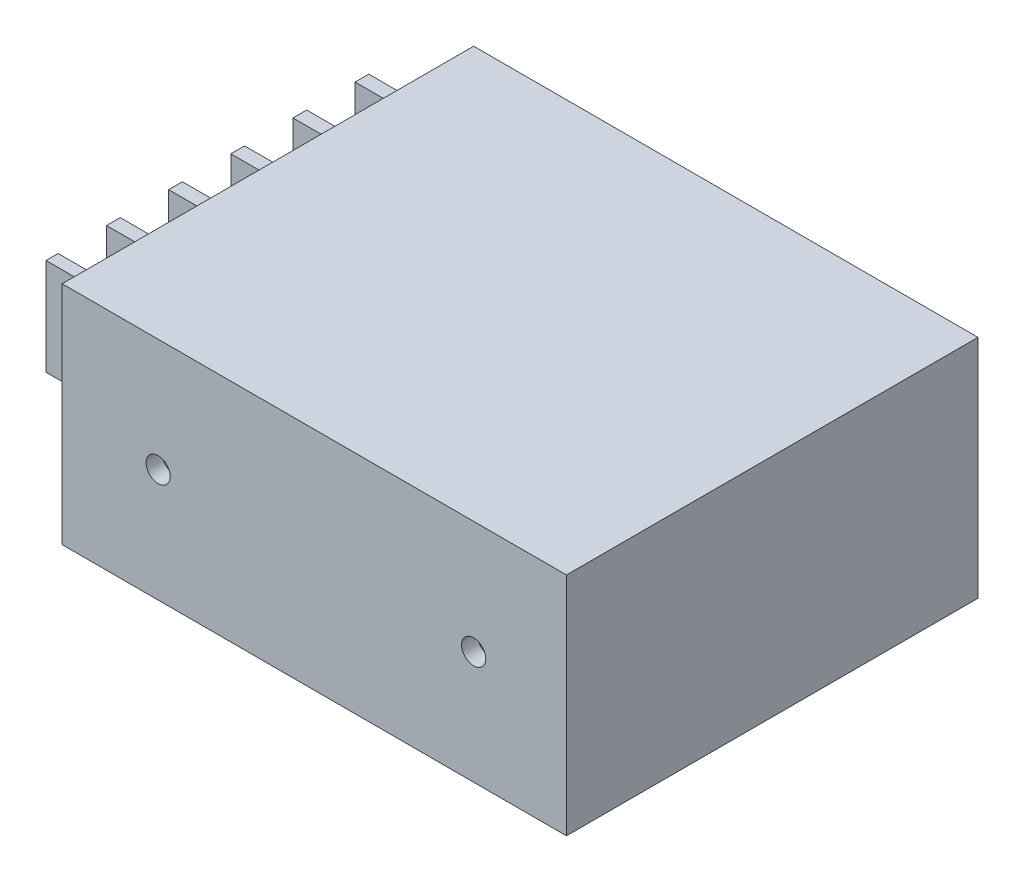
SolidWorks part; units mm, degrees
ref_plane "Спереди" through (0, 0, 0) normal (0, 0, 1) x (1, 0, 0)
ref_plane "Сверху" through (0, 0, 0) normal (0, 1, 0) x (1, 0, 0)
ref_plane "Справа" through (0, 0, 0) normal (1, 0, 0) x (0, 0, -1)
sketch "Эскиз2" plane through (0, 0, 0) normal (0, 1, 0) x (1, 0, 0)
  line L1 (-31.25, -25.5) -> (31.25, -25.5)
  line L2 (-31.25, -25.5) -> (-31.25, 25.5)
  line L3 (-31.25, 25.5) -> (31.25, 25.5)
  line L4 (31.25, -25.5) -> (31.25, 25.5)
  line L5 (-31.25, -25.5) -> (31.25, 25.5) construction
  line L6 (-31.25, 25.5) -> (31.25, -25.5) construction
  point P0 (0, 0)
  dimension "D1" = 62.5
  dimension "D2" = 51
extrude "Бобышка-Вытянуть1" add sketch "Эскиз2" along normal blind 28
sketch "Эскиз3" plane through (-31.25, 0, 0) normal (-1, 0, 0) x (0, 0, 1)
  line L0 (-25.5, 28) -> (-25.5, 0) construction
  line L1 (-25.5, 18.5) -> (14.5, 18.5)
  line L2 (-25.5, 18.5) -> (-25.5, 6.5)
  line L3 (-25.5, 6.5) -> (14.5, 6.5)
  line L4 (14.5, 18.5) -> (14.5, 6.5)
  line L5 (-25.5, 18.5) -> (14.5, 6.5) construction
  line L6 (-25.5, 6.5) -> (14.5, 18.5) construction
  line L7 (-25.5, 0) -> (25.5, 0) construction
  point P4 (-5.5, 12.5)
  dimension "D1" = 12
  dimension "D2" = 40
  dimension "D3" = 6.5
extrude "Бобышка-Вытянуть2" add sketch "Эскиз3" along normal blind 13
sketch "Эскиз4" plane through (-44.25, 0, 0) normal (-1, 0, 0) x (0, 0, 1)
  line L0 (14.5, 18.5) -> (-25.5, 18.5) construction
  line L1 (-23.8, 18.5) -> (-17.8, 18.5)
  line L2 (-23.8, 18.5) -> (-23.8, 6.5)
  line L3 (-23.8, 6.5) -> (-17.8, 6.5)
  line L4 (-17.8, 18.5) -> (-17.8, 6.5)
  line L5 (-23.8, 18.5) -> (-17.8, 6.5) construction
  line L6 (-23.8, 6.5) -> (-17.8, 18.5) construction
  line L7 (-25.5, 6.5) -> (14.5, 6.5) construction
  line L8 (-25.5, 6.5) -> (14.5, 6.5) construction
  line L9 (-16.1, 18.5) -> (-10.1, 18.5)
  line L10 (-16.1, 18.5) -> (-16.1, 6.5)
  line L11 (-16.1, 6.5) -> (-10.1, 6.5)
  line L12 (-10.1, 18.5) -> (-10.1, 6.5)
  line L13 (-16.1, 18.5) -> (-10.1, 6.5) construction
  line L14 (-16.1, 6.5) -> (-10.1, 18.5) construction
  line L15 (-8.4, 18.5) -> (-2.4, 18.5)
  line L16 (-8.4, 18.5) -> (-8.4, 6.5)
  line L17 (-8.4, 6.5) -> (-2.4, 6.5)
  line L18 (-2.4, 18.5) -> (-2.4, 6.5)
  line L19 (-8.4, 18.5) -> (-2.4, 6.5) construction
  line L20 (-8.4, 6.5) -> (-2.4, 18.5) construction
  line L21 (-25.5, 18.5) -> (-25.5, 6.5) construction
  line L22 (-0.7, 18.5) -> (5.3, 18.5)
  line L23 (-0.7, 18.5) -> (-0.7, 6.5)
  line L24 (-0.7, 6.5) -> (5.3, 6.5)
  line L25 (5.3, 18.5) -> (5.3, 6.5)
  line L26 (-0.7, 18.5) -> (5.3, 6.5) construction
  line L27 (-0.7, 6.5) -> (5.3, 18.5) construction
  line L28 (7, 18.5) -> (13, 18.5)
  line L29 (7, 18.5) -> (7, 6.5)
  line L30 (7, 6.5) -> (13, 6.5)
  line L31 (13, 18.5) -> (13, 6.5)
  line L32 (7, 18.5) -> (13, 6.5) construction
  line L33 (7, 6.5) -> (13, 18.5) construction
  point P4 (-20.8, 12.5)
  point P13 (-13.1, 12.5)
  point P18 (-5.4, 12.5)
  point P25 (2.3, 12.5)
  point P30 (10, 12.5)
  dimension "D1" = 6
  dimension "D2" = 1.7
  dimension "D4" = 1.7
  dimension "D5" = 1.7
  dimension "D6" = 1.7
  dimension "D3" = 1.7
extrude "Вырез-Вытянуть1" cut sketch "Эскиз4" against normal blind 10
sketch "Эскиз5" plane through (0, 0, 0) normal (0, -1, 0) x (1, 0, 0)
  line L1 (31.25, 25.5) -> (31.25, -25.5) construction
  circle A0 centre (-22.5, 0) radius 1.5
  circle A1 centre (16.6, 0) radius 1.5
  dimension "D3" = 3
  dimension "D1" = 14.65
  dimension "D2" = 39.1
extrude "Вырез-Вытянуть2" cut sketch "Эскиз5" against normal blind 2
sketch "Эскиз6" plane through (0, 0, 25.5) normal (0, 0, 1) x (1, 0, 0)
  line L1 (31.25, 28) -> (31.25, 0) construction
  circle A0 centre (-19.35, 14) radius 1.5
  circle A1 centre (19.75, 14) radius 1.5
  dimension "D2" = 3
  dimension "D1" = 14
  dimension "D3" = 11.5
  dimension "D4" = 39.1
extrude "Вырез-Вытянуть3" cut sketch "Эскиз6" against normal blind 2
sketch "Эскиз7" plane through (-31.25, 0, 0) normal (-1, 0, 0) x (0, 0, 1)
  line L0 (-23.7764, 21.5382) -> (13.2265, 21.5382) construction
  line L1 (-23.7764, 18.9444) -> (-17.9944, 18.9444)
  line L2 (-23.7764, 18.9444) -> (-23.7764, 27.05)
  line L3 (-23.7764, 27.05) -> (-17.9944, 27.05)
  line L4 (-17.9944, 18.9444) -> (-17.9944, 27.05)
  line L5 (-15.941, 18.9444) -> (-10.2671, 18.9444)
  line L6 (-15.941, 18.9444) -> (-15.941, 27.05)
  line L7 (-15.941, 27.05) -> (-10.2671, 27.05)
  line L8 (-10.2671, 18.9444) -> (-10.2671, 27.05)
  line L9 (-8.4839, 18.9444) -> (-2.4086, 18.9444)
  line L10 (-8.4839, 18.9444) -> (-8.4839, 27.05)
  line L11 (-8.4839, 27.05) -> (-2.4086, 27.05)
  line L12 (-2.4086, 18.9444) -> (-2.4086, 27.05)
  line L13 (-1.2173, 18.9444) -> (5.0795, 18.9444)
  line L14 (-1.2173, 18.9444) -> (-1.2173, 27.05)
  line L15 (-1.2173, 27.05) -> (5.0795, 27.05)
  line L16 (5.0795, 18.9444) -> (5.0795, 27.05)
  line L17 (6.6374, 18.9444) -> (13.2265, 18.9444)
  line L18 (6.6374, 18.9444) -> (6.6374, 27.05)
  line L19 (6.6374, 27.05) -> (13.2265, 27.05)
  line L20 (13.2265, 18.9444) -> (13.2265, 27.05)
  text T0 " L   N   G  -V  +V" font "Arial" height in points 14
extrude "Вырез-Вытянуть4" cut sketch "Эскиз7" against normal blind 0.2
sketch "Эскиз8" plane through (-34.25, 0, 0) normal (-1, 0, 0) x (0, 0, 1)
  line L0 (-20.9124, 12.514) -> (10.0509, 12.514) construction
  circle A0 centre (-20.9124, 12.514) radius 0.1
  circle A1 centre (-13.3472, 12.514) radius 0.1
  circle A2 centre (-5.2416, 12.514) radius 0.1
  circle A3 centre (2.0534, 12.514) radius 0.1
  circle A4 centre (10.0509, 12.514) radius 0.1
  dimension "D1" = 0.2
extrude "Вырез-Вытянуть5" cut sketch "Эскиз8" against normal blind 0.2
equation "\"D4@Эскиз4\"=\"D2@Эскиз4\""
equation "\"D5@Эскиз4\"=\"D2@Эскиз4\""
equation "\"D6@Эскиз4\"=\"D2@Эскиз4\""
equation "\"D3@Эскиз4\"=\"D2@Эскиз4\""
